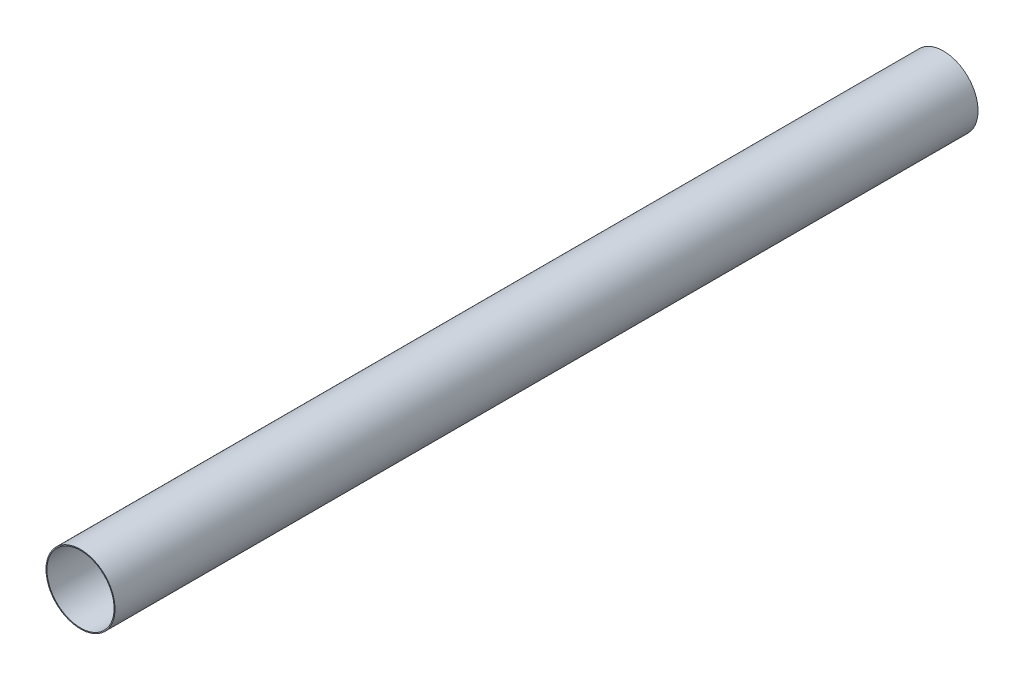
SolidWorks part; units mm, degrees
material "Glass"
ref_plane "Front Plane" through (0, 0, 0) normal (0, 0, 1) x (1, 0, 0)
ref_plane "Top Plane" through (0, 0, 0) normal (0, 1, 0) x (1, 0, 0)
ref_plane "Right Plane" through (0, 0, 0) normal (1, 0, 0) x (0, 0, -1)
sketch "Sketch1" plane through (0, 0, 0) normal (0, 0, 1) x (1, 0, 0)
  circle A0 centre (0, 0) radius 50.8
  circle A1 centre (0, 0) radius 49.403
  dimension "D1" = 98.806
  dimension "D2" = 101.6
extrude "Boss-Extrude1" add sketch "Sketch1" along normal blind 1270
